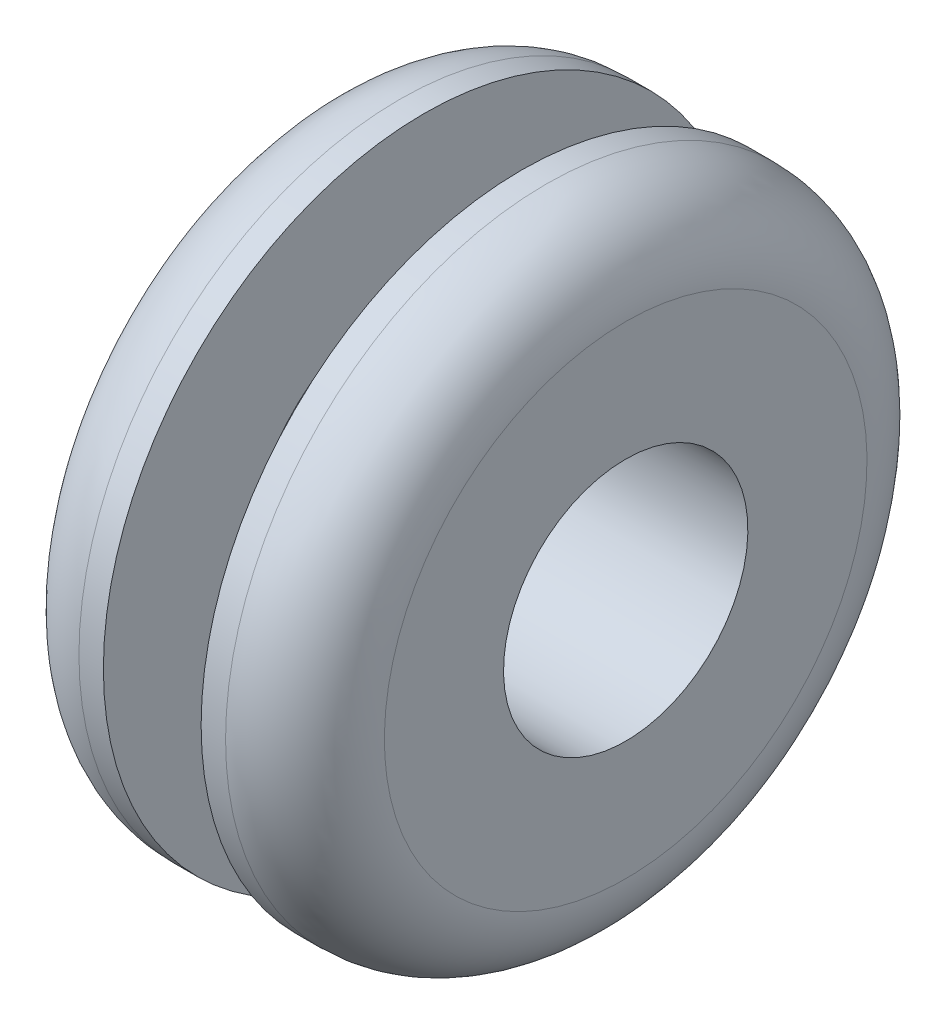
SolidWorks part; units mm, degrees
ref_plane "Спереди(Плоскость XY)" through (0, 0, 0) normal (0, 0, 1) x (1, 0, 0)
ref_plane "Сверху(Плоскость XZ)" through (0, 0, 0) normal (0, 1, 0) x (1, 0, 0)
ref_plane "Справа(Плоскость ZY)" through (0, 0, 0) normal (1, 0, 0) x (0, 0, -1)
sketch "Эскиз1" plane through (0, 0, 0) normal (0, 0, 1) x (1, 0, 0)
  line L0 (0, 0) -> (0, 1) construction
  line L1 (-0.8, 1) -> (0.8, 1)
  line L2 (-0.8, 1) -> (-0.8, 3.25)
  line L3 (-0.8, 3.25) -> (-2.5, 3.25)
  line L4 (-2.5, 3.25) -> (-2.5, 0)
  line L5 (-2.5, 0) -> (2.5, 0)
  line L6 (0.8, 1) -> (0.8, 3.25)
  line L7 (0.8, 3.25) -> (2.5, 3.25)
  line L8 (2.5, 3.25) -> (2.5, 0)
  line L9 (0, 0) -> (0, -2) construction
  line L10 (0, -2) -> (-6.7744, -2) construction
  point P5 (0, 1)
  dimension "D1" = 2
  dimension "D2" = 5.25
  dimension "D3" = 1.6
  dimension "D4" = 3
  dimension "D5" = 5
sketch "Эскиз3" plane through (0, 0, 0) normal (1, 0, 0) x (0, 0, -1)
  line L1 (0, 0) -> (0, -2) construction
  line L2 (-1, -1.2) -> (1, -1.2) construction
  line L3 (-1, 0) -> (1, 0)
  line L4 (-1, -2.4) -> (1, -2.4)
  line L5 (0, 0) -> (1.5, 0) construction
  arc A0 (-1, 0) -> (-1, -2.4) centre (-1, -1.2) ccw
  arc A1 (1, -2.4) -> (1, 0) centre (1, -1.2) ccw
  circle A2 centre (1, -1.2) radius 1.2 construction
  circle A4 centre (0, -2) radius 2 construction
  point P7 (0, -1.2)
  dimension "D3" = 2
  dimension "D2" = 2.4
revolve "Повернуть1" add sketch "Эскиз1" angle 360 about L10
fillet "Скругление1" radius 1.3 2 edges at (-2.5, 3.25, 0) (2.5, 3.25, 0)
